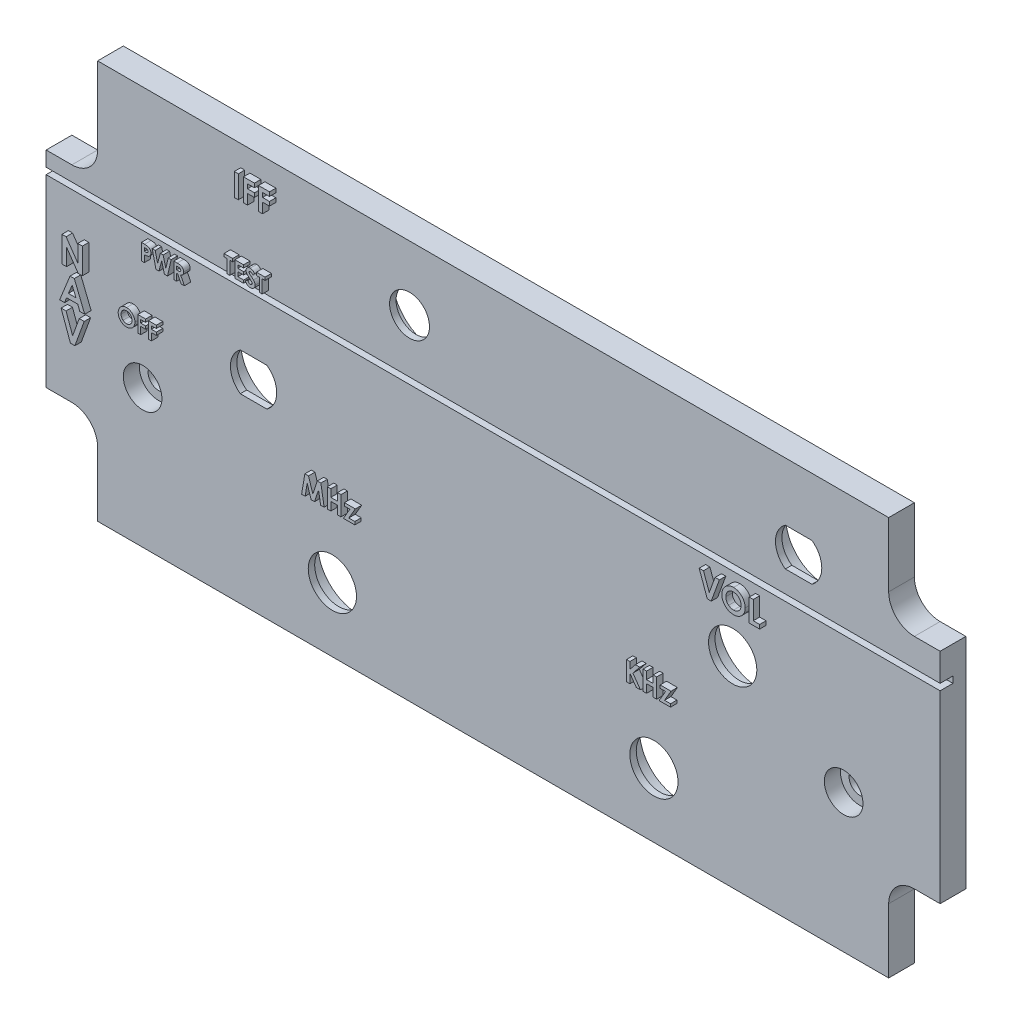
SolidWorks part; units mm, degrees
ref_plane "Front Plane" through (0, 0, 0) normal (0, 0, 1) x (1, 0, 0)
ref_plane "Top Plane" through (0, 0, 0) normal (0, 1, 0) x (1, 0, 0)
ref_plane "Right Plane" through (0, 0, 0) normal (1, 0, 0) x (0, 0, -1)
sketch "Sketch1" plane through (0, 0, 0) normal (0, 0, 1) x (1, 0, 0)
  line L0 (39.5, 10) -> (99.5, 10) construction
  line L1 (8, 0) -> (131, 0)
  line L2 (0, 14) -> (0, 46)
  line L3 (8, 62) -> (131, 62)
  line L4 (139, 14) -> (139, 48)
  line L5 (69.5, 62) -> (69.5, 0) construction
  line L13 (8, 62) -> (8, 50)
  line L14 (4, 46) -> (0, 46)
  line L15 (8, 0) -> (8, 10)
  line L16 (4, 14) -> (0, 14)
  line L17 (131, 62) -> (131, 52)
  line L18 (135, 48) -> (139, 48)
  line L19 (131, 0) -> (131, 10)
  line L20 (135, 14) -> (139, 14)
  line L21 (0, 30) -> (139, 30) construction
  line L22 (0, 0) -> (131, 0) construction
  line L23 (0, 0) -> (0, 64.6609) construction
  line L31 (30.1866, 28.2676) -> (34.3134, 28.2676) construction
  line L32 (34.3134, 34.1676) -> (30.1866, 34.1676) construction
  line L33 (30.1866, 28.2676) -> (34.3134, 28.2676)
  line L34 (34.3134, 34.1676) -> (30.1866, 34.1676)
  line L39 (114.9366, 47.05) -> (119.0634, 47.05)
  line L40 (119.0634, 52.95) -> (114.9366, 52.95)
  line L41 (114.9366, 47.05) -> (119.0634, 47.05)
  line L42 (119.0634, 52.95) -> (114.9366, 52.95)
  arc A8 (8, 10) -> (4, 14) centre (4, 10) ccw
  arc A9 (8, 50) -> (4, 46) centre (4, 50) cw
  arc A11 (131, 10) -> (135, 14) centre (135, 10) cw
  arc A12 (131, 52) -> (135, 48) centre (135, 52) ccw
  circle A15 centre (44.5, 10) radius 3.75 construction
  circle A16 centre (94.5, 10) radius 3.75 construction
  circle A17 centre (106.75, 31.2176) radius 3.75 construction
  circle A18 centre (15, 21.5) radius 1.65 construction
  circle A19 centre (124, 21.5) radius 1.65 construction
  circle A20 centre (15, 21.5) radius 1.65
  circle A21 centre (124, 21.5) radius 1.65
  circle A22 centre (106.75, 31.2176) radius 3.75
  circle A23 centre (94.5, 10) radius 3.75
  circle A24 centre (44.5, 10) radius 3.75
  circle A27 centre (56.5, 52) radius 3.1 construction
  circle A29 centre (56.5, 52) radius 3.1
  arc A43 (34.3134, 28.2676) -> (34.3134, 34.1676) centre (32.25, 31.2176) ccw construction
  arc A44 (30.1866, 34.1676) -> (30.1866, 28.2676) centre (32.25, 31.2176) ccw construction
  arc A45 (34.3134, 28.2676) -> (34.3134, 34.1676) centre (32.25, 31.2176) ccw
  arc A46 (30.1866, 34.1676) -> (30.1866, 28.2676) centre (32.25, 31.2176) ccw
  arc A51 (119.0634, 47.05) -> (119.0634, 52.95) centre (117, 50) ccw
  arc A52 (114.9366, 52.95) -> (114.9366, 47.05) centre (117, 50) ccw
  arc A53 (119.0634, 47.05) -> (119.0634, 52.95) centre (117, 50) ccw
  arc A54 (114.9366, 52.95) -> (114.9366, 47.05) centre (117, 50) ccw
  point P13 (69.5, 10)
  point P21 (131, 14)
  point P25 (8, 46)
  point P40 (131, 48)
  point P55 (2, 46)
  dimension "D3" = 30
  dimension "D4" = 14
  dimension "D5" = 16
  dimension "D8" = 4
  dimension "D12" = 4
  dimension "D13" = 0
  dimension "D6" = 60
  dimension "D7" = 10
  dimension "D11" = 8
  dimension "D15" = 123
  dimension "D16" = 139
  dimension "D20" = 62
  dimension "D22" = 8
  dimension "D9" = 8
  dimension "D10" = 14
extrude "Boss-Extrude1" add sketch "Sketch1" along normal blind 4
sketch "Sketch2" plane through (0, 0, 0) normal (0, 0, -1) x (-1, 0, 0)
  line L0 (-119.0634, 52.95) -> (-114.9366, 52.95) construction
  line L1 (-114.9366, 47.05) -> (-119.0634, 47.05) construction
  line L24 (-4, 16) -> (-2, 16)
  line L25 (-2, 16) -> (-2, 44)
  line L26 (-2, 44) -> (-4, 44)
  line L27 (-10, 50) -> (-10, 60)
  line L28 (-10, 60) -> (-129, 60)
  line L29 (-129, 60) -> (-129, 52)
  line L30 (-135, 46) -> (-137, 46)
  line L31 (-137, 46) -> (-137, 16)
  line L32 (-137, 16) -> (-135, 16)
  line L33 (-129, 10) -> (-129, 2)
  line L34 (-129, 2) -> (-10, 2)
  line L35 (-10, 2) -> (-10, 10)
  line L36 (-4, 16) -> (-2, 16)
  line L37 (-2, 16) -> (-2, 44)
  line L38 (-2, 44) -> (-4, 44)
  line L39 (-10, 50) -> (-10, 60)
  line L40 (-10, 60) -> (-129, 60)
  line L41 (-129, 60) -> (-129, 52)
  line L42 (-135, 46) -> (-137, 46)
  line L43 (-137, 46) -> (-137, 16)
  line L44 (-137, 16) -> (-135, 16)
  line L45 (-129, 10) -> (-129, 2)
  line L46 (-129, 2) -> (-10, 2)
  line L47 (-10, 2) -> (-10, 10)
  circle A5 centre (-44.5, 10) radius 3.75 construction
  circle A6 centre (-94.5, 10) radius 3.75 construction
  circle A7 centre (-106.75, 31.2176) radius 3.75 construction
  circle A9 centre (-44.5, 10) radius 3.75 construction
  circle A10 centre (-94.5, 10) radius 3.75 construction
  circle A11 centre (-106.75, 31.2176) radius 3.75 construction
  circle A13 centre (-44.5, 10) radius 6.25
  circle A14 centre (-94.5, 10) radius 6.25
  circle A15 centre (-106.75, 31.2176) radius 6.25
  arc A16 (-119.0634, 52.95) -> (-119.0634, 47.05) centre (-117, 50) ccw construction
  circle A18 centre (-56.5, 52) radius 3.1 construction
  circle A19 centre (-56.5, 52) radius 3.1 construction
  arc A20 (-114.9366, 47.05) -> (-114.9366, 52.95) centre (-117, 50) ccw construction
  arc A21 (-119.0634, 52.95) -> (-119.0634, 47.05) centre (-117, 50) ccw construction
  arc A22 (-114.9366, 47.05) -> (-114.9366, 52.95) centre (-117, 50) ccw construction
  arc A23 (-119.0634, 52.95) -> (-114.9366, 52.95) centre (-117, 50) cw construction
  circle A24 centre (-56.5, 52) radius 6.75
  arc A26 (-119.0634, 47.05) -> (-114.9366, 47.05) centre (-117, 50) ccw construction
  arc A27 (-120.439, 54.9167) -> (-113.561, 54.9167) centre (-117, 50) cw
  arc A28 (-4, 16) -> (-10, 10) centre (-4, 10) ccw
  arc A29 (-10, 50) -> (-4, 44) centre (-4, 50) ccw
  arc A30 (-135, 46) -> (-129, 52) centre (-135, 52) ccw
  arc A31 (-129, 10) -> (-135, 16) centre (-135, 10) ccw
  arc A32 (-4, 16) -> (-10, 10) centre (-4, 10) ccw
  arc A33 (-10, 50) -> (-4, 44) centre (-4, 50) ccw
  arc A34 (-135, 46) -> (-129, 52) centre (-135, 52) ccw
  arc A35 (-129, 10) -> (-135, 16) centre (-135, 10) ccw
  arc A36 (-120.439, 54.9167) -> (-120.439, 45.0833) centre (-117, 50) ccw
  arc A37 (-120.439, 45.0833) -> (-113.561, 45.0833) centre (-117, 50) ccw
  arc A38 (-113.561, 45.0833) -> (-113.561, 54.9167) centre (-117, 50) ccw
  arc A39 (-30.1866, 28.2676) -> (-30.1866, 34.1676) centre (-32.25, 31.2176) ccw construction
  circle A40 centre (-32.25, 31.2176) radius 3.6 construction
  circle A41 centre (-32.25, 31.2176) radius 6
  dimension "D1" = 2.5
  dimension "D2" = 2.4
  dimension "D6" = 12
  dimension "D4" = 13.5
  dimension "D3" = 2
  dimension "D5" = 2.4
extrude "Back holes" cut sketch "Sketch2" against normal blind 3
sketch "Sketch3" plane through (0, 0, 4) normal (0, 0, 1) x (1, 0, 0)
  circle A0 centre (124, 21.5) radius 1.65 construction
  circle A1 centre (15, 21.5) radius 1.65 construction
  circle A2 centre (124, 21.5) radius 1.65 construction
  circle A3 centre (15, 21.5) radius 1.65 construction
  circle A4 centre (15, 21.5) radius 3
  circle A5 centre (124, 21.5) radius 3
  dimension "D1" = 6
extrude "Cut-Extrude2" cut sketch "Sketch3" against normal blind 2.5
sketch "Sketch5" plane through (0, 0, 4) normal (0, 0, 1) x (1, 0, 0)
  line L0 (139, 42.6747) -> (0, 42.6747)
  line L1 (139, 14) -> (139, 48) construction
  line L2 (0, 46) -> (0, 14) construction
  line L3 (0, 42.6747) -> (0, 43.6747)
  line L4 (0, 43.6747) -> (139, 43.6747)
  line L5 (139, 43.6747) -> (139, 42.6747)
  dimension "D1" = 1
extrude "Cut-Extrude3" cut sketch "Sketch5" against normal blind 2
sketch "Sketch4" plane through (0, 0, 4) normal (0, 0, 1) x (1, 0, 0)
  line L0 (6.5219, 26.9631) -> (6.5219, 14.5758) construction
  line L2 (33.1689, 20.5068) -> (113.2155, 20.5068) construction
  line L3 (-3.8412, 32.8725) -> (13.9628, 32.8725) construction
  line L4 (-4.2039, 27.8725) -> (13.9628, 27.8725) construction
  line L5 (-4.2039, 22.8725) -> (13.9628, 22.8725) construction
  line L6 (3.5219, 33.1522) -> (3.5219, -6.8271) construction
  text T0 "N" font "Century Gothic" height 4
  text T1 "<b>OFF</b>" font "Century Gothic" height 2.5
  text T2 "<b>PWR</b>" font "Century Gothic" height 2.5
  text T3 "<b>TEST</b>" font "Century Gothic" height 2.5
  text T4 "<b>VOL</b>" font "Century Gothic" height 3.5
  text T5 "MHz" font "Century Gothic" height 3
  text T6 "KHz" font "Century Gothic" height 3
  text T7 "A" font "Century Gothic" height 4
  text T8 "V" font "Century Gothic" height 4
  text T9 "IFF" font "Century Gothic" height 3.5
  dimension "D1" = 5
  dimension "D2" = 5
  dimension "D3" = 3
extrude "Textos" add sketch "Sketch4" along normal blind 1
